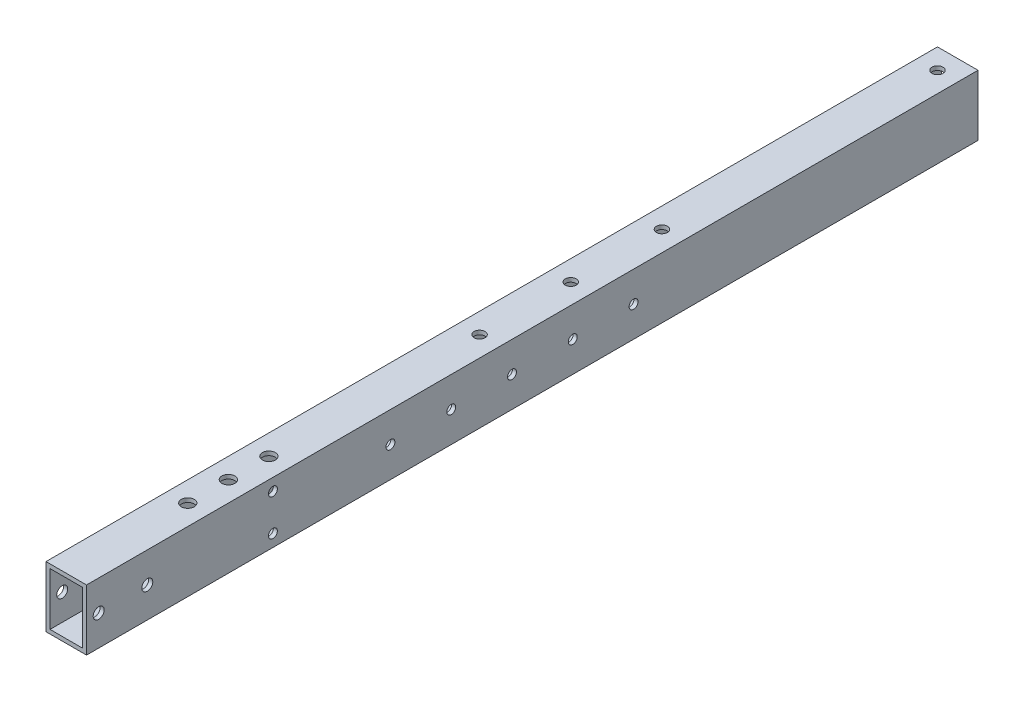
SolidWorks part; units mm, degrees
material "6061 合金"
ref_plane "前视基准面" through (0, 0, 0) normal (0, 0, 1) x (1, 0, 0)
ref_plane "上视基准面" through (0, 0, 0) normal (0, 1, 0) x (1, 0, 0)
ref_plane "右视基准面" through (0, 0, 0) normal (1, 0, 0) x (0, 0, -1)
sketch "草图1" plane through (0, 0, 0) normal (0, 1, 0) x (1, 0, 0)
  line L0 (0, 0) -> (-12.5, 0)
  line L1 (-12.5, 5) -> (-12.5, -66)
  dimension "D1" = 12.5
  dimension "D2" = 71
  dimension "D3" = 5
other "方形管 20 X 20 X 2(1)"
ref_plane "基准面1" through (0, 0, 0) normal (-1, 0, 0) x (0, 0, 1)
sketch "Sketch1" plane through (0, 0, 0) normal (-1, 0, 0) x (0, 0, 1)
  line L0 (4, -6.5) -> (4, 6.5)
  line L1 (5, -7.5) -> (-5, -7.5)
  line L2 (5, -7.5) -> (5, 7.5)
  line L3 (5, 7.5) -> (-5, 7.5)
  line L4 (-5, -7.5) -> (-5, 7.5)
  line L5 (0, 7.5) -> (0, -7.5) construction
  line L6 (5, 0) -> (-5, 0) construction
  line L7 (4, 6.5) -> (-4, 6.5)
  line L8 (-4, -6.5) -> (-4, 6.5)
  line L9 (4, -6.5) -> (-4, -6.5)
  point P0 (0, 0)
  point P4 (0, 0)
  point P33 (0, 0)
  dimension "D1" = 10
  dimension "D2" = 15
  dimension "D3" = 1
other "方形管 20 X 20 X 2(8)"
ref_plane "基准面4" through (-12.5, 0, -5) normal (0, 0, 1) x (1, 0, 0)
sketch "Sketch14" plane through (-12.5, 0, -5) normal (0, 0, 1) x (1, 0, 0)
  line L0 (0, 7.5) -> (0, -7.5) construction
  line L1 (-12.5, 7.5) -> (12.5, 7.5)
  line L2 (-12.5, 7.5) -> (-12.5, -7.5)
  line L3 (-12.5, -7.5) -> (12.5, -7.5)
  line L4 (12.5, 7.5) -> (12.5, -7.5)
  line L5 (0, -7.5) -> (0, 7.5) construction
  line L6 (-12.5, 0) -> (12.5, 0) construction
  line L7 (0, -7.5) -> (12.5, -7.5) construction
  line L8 (-11.5, -6.5) -> (11.5, -6.5)
  line L9 (11.5, 6.5) -> (11.5, -6.5)
  line L10 (-11.5, 6.5) -> (11.5, 6.5)
  line L11 (-11.5, 6.5) -> (-11.5, -6.5)
  point P0 (0, 0)
  point P4 (0, 0)
  point P33 (0, 0)
  dimension "D1" = 25
  dimension "D2" = 1
other "剪裁/延伸1"
sketch "草图6" [suppressed] plane through (0, 0, 15) normal (0, 0, 1) x (1, 0, 0)
  line L0 (0, 0) -> (-14, 0) construction
  line L2 (-14, 0) -> (-14, -10) construction
  line L3 (-19, -5) -> (-9, -5)
  line L4 (-19, -5) -> (-19, 5)
  line L6 (-19, 5) -> (-9, 5)
  line L7 (-9, -5) -> (-9, 5)
  line L8 (-14, 5) -> (-14, -5) construction
  line L9 (-19, 0) -> (-9, 0) construction
  circle A0 centre (-23, 5) radius 1.5
  circle A1 centre (-5, 5) radius 1.5
  circle A2 centre (-5, -5) radius 1.5
  circle A3 centre (-23, -5) radius 1.5
  dimension "D3" = 3
  dimension "D1" = 18
  dimension "D2" = 10
  dimension "D4" = 14
  dimension "D5" = 10
  dimension "D6" = 10
extrude "切除-拉伸1" [suppressed] cut sketch "草图6" against normal through all
sketch "草图7" plane through (0, -7.5, 0) normal (0, -1, 0) x (1, 0, 0)
  line L0 (-25, -5) -> (0, -5) construction
  line L1 (-21.5, -5) -> (-3.5, -5)
  line L2 (-21.5, -5) -> (-21.5, 35)
  line L3 (-21.5, 35) -> (-3.5, 35)
  line L4 (-3.5, -5) -> (-3.5, 35)
  line L5 (-12.5, 35) -> (-12.5, -5) construction
  line L6 (-21.5, 15) -> (-3.5, 15) construction
  point P212 (-12.5, 15)
  dimension "D1" = 40
  dimension "D2" = 18
extrude "切除-拉伸2" [suppressed] cut sketch "草图7" against normal up to next
sketch "草图8" plane through (0, 0, -5) normal (0, 0, 1) x (1, 0, 0)
  line L0 (0, 7.5) -> (0, -7.5) construction
  line L1 (10, -7.5) -> (0, -7.5)
  line L2 (10, -7.5) -> (10, 7.5)
  line L3 (10, 7.5) -> (0, 7.5)
  line L4 (0, -7.5) -> (0, 7.5)
  line L5 (5, 7.5) -> (5, -7.5) construction
  line L6 (10, 0) -> (0, 0) construction
  line L7 (9, -6.5) -> (9, 6.5)
  line L8 (9, 6.5) -> (1, 6.5)
  line L9 (1, -6.5) -> (1, 6.5)
  line L10 (9, -6.5) -> (1, -6.5)
  point P116 (5, 0)
  dimension "D1" = 0
  dimension "D2" = 10
  dimension "D3" = 15
  dimension "D4" = 1
extrude "凸台-拉伸1" add sketch "草图8" along normal blind 220 separate body
sketch "草图9" plane through (0, 7.5, 0) normal (0, 1, 0) x (1, 0, 0)
  line L0 (-12.5, -66) -> (-12.5, 5) construction
  line L1 (10, -215) -> (10, 5) construction
  line L2 (0, 5) -> (-25, 5) construction
  line L3 (10, -30.5) -> (-25, -30.5) construction
  line L4 (-18.5, -12) -> (-18.5, -19)
  line L5 (-18.5, -42) -> (-14.5, -42)
  line L6 (-6.5, -49) -> (-10.5, -49)
  line L7 (-6.5, -49) -> (-6.5, -42)
  line L8 (-6.5, -42) -> (-10.5, -42)
  line L9 (-10.5, -49) -> (-10.5, -42)
  line L10 (-8.5, -42) -> (-8.5, -49) construction
  line L11 (-6.5, -45.5) -> (-10.5, -45.5) construction
  line L16 (-14.5, -49) -> (-14.5, -42)
  line L17 (-18.5, -49) -> (-14.5, -49)
  line L18 (-18.5, -49) -> (-18.5, -42)
  line L27 (-18.5, -12) -> (-14.5, -12)
  line L28 (5, -113) -> (5, -68) construction
  line L29 (0, -66) -> (-25, -66) construction
  line L30 (10, -46) -> (-25, -46) construction
  line L31 (-25, -66) -> (-25, 5) construction
  line L32 (-14.5, -12) -> (-14.5, -19)
  line L33 (-18.5, -19) -> (-14.5, -19)
  line L34 (-6.5, -19) -> (-10.5, -19)
  line L35 (-10.5, -12) -> (-10.5, -19)
  line L36 (-6.5, -12) -> (-10.5, -12)
  line L37 (-6.5, -12) -> (-6.5, -19)
  line L38 (10, 5) -> (0, 5) construction
  line L39 (-25, 5) -> (0, 5) construction
  line L41 (0, -215) -> (0, 5) construction
  line L42 (0, 5) -> (10, 5) construction
  line L43 (5, -175) -> (10, -175) construction
  line L44 (10, -215) -> (10, 5) construction
  line L45 (0, -215) -> (10, -215) construction
  line L46 (5, -215) -> (5, -175) construction
  line L47 (5, 0) -> (5, 5) construction
  line L48 (10, -215) -> (0, -215) construction
  circle A0 centre (-4, -48.5) radius 1.05
  circle A2 centre (-21, -48.5) radius 1.05
  circle A5 centre (-21, -12.5) radius 1.05
  circle A6 centre (-4, -12.5) radius 1.05
  circle A7 centre (-4.5, -61) radius 1.35
  circle A8 centre (-20.5, -61) radius 1.35
  circle A9 centre (5, -68) radius 1.35
  circle A10 centre (5, -90.5) radius 1.35
  circle A11 centre (5, -113) radius 1.35
  circle A12 centre (5, -175) radius 1.6
  circle A14 centre (-22, 0) radius 1.35
  circle A16 centre (5, 0) radius 1.35
  circle A17 centre (-3, 0) radius 1.35
  circle A18 centre (5, -185) radius 1.6
  circle A19 centre (5, -165) radius 1.6
  point P114 (-8.5, -45.5)
  dimension "D2" = 2.1
  dimension "D12" = 2.7
  dimension "D13" = 73
  dimension "D17" = 3.2
  dimension "D20" = 5
  dimension "D21" = 5
  dimension "D1" = 8.5
  dimension "D3" = 20
  dimension "D4" = 4
  dimension "D5" = 4
  dimension "D6" = 7
  dimension "D7" = 3
  dimension "D8" = 4
  dimension "D9" = 30
  dimension "D10" = 16
  dimension "D11" = 5
  dimension "D15" = 22.5
  dimension "D16" = 5
  dimension "D18" = 20
  dimension "D19" = 40
  dimension "D24" = 9.5
  dimension "D14" = 3
extrude "切除-拉伸3" cut sketch "草图9" against normal through all
sketch "草图10" plane through (0, 7.5, 0) normal (0, 1, 0) x (1, 0, 0)
  line L0 (-12.5, -38) -> (-12.5, -66) construction
  line L1 (-6.5, -38) -> (-18.5, -38)
  line L2 (-6.5, -38) -> (-6.5, -23)
  line L3 (-6.5, -23) -> (-18.5, -23)
  line L4 (-18.5, -38) -> (-18.5, -23)
  line L5 (0, -66) -> (-25, -66) construction
  line L6 (-16.5, -42) -> (-16.5, -19) construction
  line L7 (-14.5, -42) -> (-18.5, -42) construction
  line L8 (-18.5, -19) -> (-14.5, -19) construction
  line L9 (-18.5, -30.5) -> (-16.5, -30.5) construction
  dimension "D1" = 12
  dimension "D2" = 15
extrude "切除-拉伸4" cut sketch "草图10" against normal up to next (1 mm away)
sketch "草图11" plane through (10, 0, 0) normal (1, 0, 0) x (0, 0, -1)
  line L0 (-215, 0) -> (5, 0) construction
  line L1 (-215, -7.5) -> (-215, 7.5) construction
  line L2 (5, -7.5) -> (5, 7.5) construction
  line L3 (-169, -4.5) -> (-169, 4.5) construction
  circle A0 centre (-65, 0) radius 1.1 construction
  circle A1 centre (-80, 0) radius 1.1
  circle A2 centre (-95, 0) radius 1.1
  circle A3 centre (-110, 0) radius 1.1
  circle A4 centre (-125, 0) radius 1.1
  circle A5 centre (-140, 0) radius 1.1
  circle A6 centre (-212, 0) radius 1.35
  circle A7 centre (-200, 0) radius 1.35
  circle A8 centre (-169, -4.5) radius 1.1
  circle A10 centre (-169, 4.5) radius 1.1
  dimension "D1" = 70
  dimension "D2" = 2.2
  dimension "D4" = 15
  dimension "D6" = 3
  dimension "D7" = 2.7
  dimension "D8" = 9
  dimension "D10" = 2.2
  dimension "D5" = 12
  dimension "D9" = 46
  dimension "D3" = 6
extrude "切除-拉伸5" cut sketch "草图11" against normal through all
delete or keep bodies "实体-删除/保留 1" type delete bodies bodies 121
sketch "草图13" plane through (0, 0, 0) normal (-1, 0, 0) x (0, 0, 1)
  line L0 (215, -7.5) -> (-5, -7.5) construction
  line L1 (215, 7.5) -> (163, 7.5)
  line L2 (215, 7.5) -> (215, -7.5)
  line L3 (215, -7.5) -> (163, -7.5)
  line L4 (163, 7.5) -> (163, -7.5)
  circle A0 centre (169, -4.5) radius 1.1 construction
  circle A1 centre (169, 4.5) radius 1.1 construction
  circle A2 centre (169, -4.5) radius 1.1
  circle A3 centre (169, 4.5) radius 1.1
  dimension "D1" = 52
extrude "凸台-拉伸2" [suppressed] add sketch "草图13" along normal blind 1 separate body
sketch "草图14" plane through (0, 7.5, 0) normal (0, 1, 0) x (1, 0, 0)
  line L0 (0, 5) -> (-25, 5) construction
  line L1 (-25, -66) -> (0, -66)
  line L2 (-25, -66) -> (-25, 5)
  line L3 (-25, 5) -> (0, 5)
  line L4 (0, -66) -> (0, 5)
  line L5 (-12.5, 5) -> (-12.5, -66) construction
  line L6 (-25, -30.5) -> (0, -30.5) construction
  line L7 (0, -215) -> (0, 5) construction
  line L8 (0, -66) -> (-25, -66) construction
  point P168 (-12.5, -30.5)
extrude "切除-拉伸6" cut sketch "草图14" against normal through all
